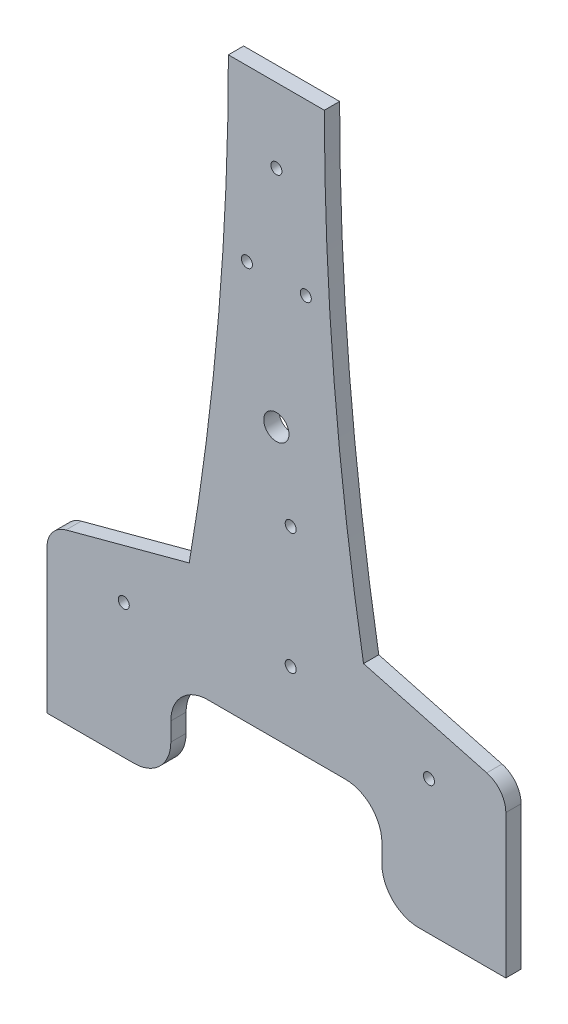
SolidWorks part; units mm, degrees
ref_plane "Plano frontal" through (0, 0, 0) normal (0, 0, 1) x (1, 0, 0)
ref_plane "Plano superior" through (0, 0, 0) normal (0, 1, 0) x (1, 0, 0)
ref_plane "Plano direito" through (0, 0, 0) normal (1, 0, 0) x (0, 0, -1)
sketch "Esboço2" plane through (0, 0, 0) normal (0, 0, 1) x (1, 0, 0)
  line L1 (0, 0) -> (23.7, 0)
  line L2 (0, 0) -> (0, 38.9591)
  line L6 (33.7, 10) -> (33.7, 15)
  line L7 (43.7, 25) -> (81.1, 25)
  line L9 (5.1883, 45.7206) -> (38.7, 54.7)
  line L13 (62.4, 0) -> (62.4, 179.7) construction
  line L14 (49.35, 179.7) -> (75.45, 179.7)
  line L16 (119.6117, 45.7206) -> (86.1, 54.7)
  line L17 (91.1, 10) -> (91.1, 15)
  line L18 (124.8, 0) -> (124.8, 38.9591)
  line L19 (124.8, 0) -> (101.1, 0)
  line L20 (86.1, 54.7) -> (124.8, 54.7) construction
  line L21 (52.9, 133.5) -> (47.9042, 133.5) construction
  arc A0 (75.45, 179.7) -> (86.1, 54.7) centre (814.3431, 179.7) ccw
  arc A1 (49.35, 179.7) -> (38.7, 54.7) centre (-689.5431, 179.7) cw
  arc A2 (119.6117, 45.7206) -> (124.8, 38.9591) centre (117.8, 38.9591) cw
  arc A3 (5.1883, 45.7206) -> (0, 38.9591) centre (7, 38.9591) ccw
  arc A4 (91.1, 10) -> (101.1, 0) centre (101.1, 10) ccw
  arc A5 (91.1, 15) -> (81.1, 25) centre (81.1, 15) ccw
  arc A6 (23.7, 0) -> (33.7, 10) centre (23.7, 10) ccw
  arc A7 (33.7, 15) -> (43.7, 25) centre (43.7, 15) cw
  circle A8 centre (62.4, 159.5) radius 1.5
  circle A9 centre (54.4, 133.5) radius 1.5
  circle A10 centre (70.4, 133.5) radius 1.5
  circle A11 centre (62.4, 98.575) radius 3.425
  circle A12 centre (66.3, 77.1) radius 1.5
  circle A13 centre (66.3, 44.1) radius 1.5
  circle A14 centre (103.9, 36.5) radius 1.5
  circle A15 centre (20.9, 36.5) radius 1.5
  point P14 (62.4, 25)
  point P20 (124.8, 44.3304)
  point P24 (0, 44.3304)
  point P27 (91.1, 0)
  point P30 (91.1, 25)
  point P33 (33.7, 0)
  point P36 (33.7, 25)
  point P53 (68.9, 133.5)
  point P54 (62.4, 161)
  point P55 (54.4, 135)
  point P56 (55.9, 133.5)
  point P57 (62.4, 158)
  point P60 (54.4, 132)
  point P61 (62.4, 102)
  point P62 (66.3, 45.6)
  point P63 (66.3, 42.6)
  point P64 (66.3, 25)
  point P65 (102.4, 36.5)
  point P66 (66.3, 75.6)
  point P67 (20.9, 35)
  point P69 (22.4, 36.5)
  point P70 (0, 0)
  point P71 (64.8, 44.1)
  dimension "D7" = 125
  dimension "D9" = 7
  dimension "D10" = 10
  dimension "D11" = 3
  dimension "D15" = 6.85
  dimension "D1" = 124.8
  dimension "D2" = 33.7
  dimension "D3" = 25
  dimension "D4" = 154.7
  dimension "D5" = 26.1
  dimension "D6" = 47.4
  dimension "D8" = 15
  dimension "D12" = 18.7
  dimension "D13" = 13
  dimension "D14" = 23
  dimension "D16" = 30
  dimension "D17" = 30
  dimension "D18" = 17.6
  dimension "D19" = 60
  dimension "D20" = 80
  dimension "D21" = 35
extrude "Ressalto-extrusão1" add sketch "Esboço2" along normal blind 4.15
